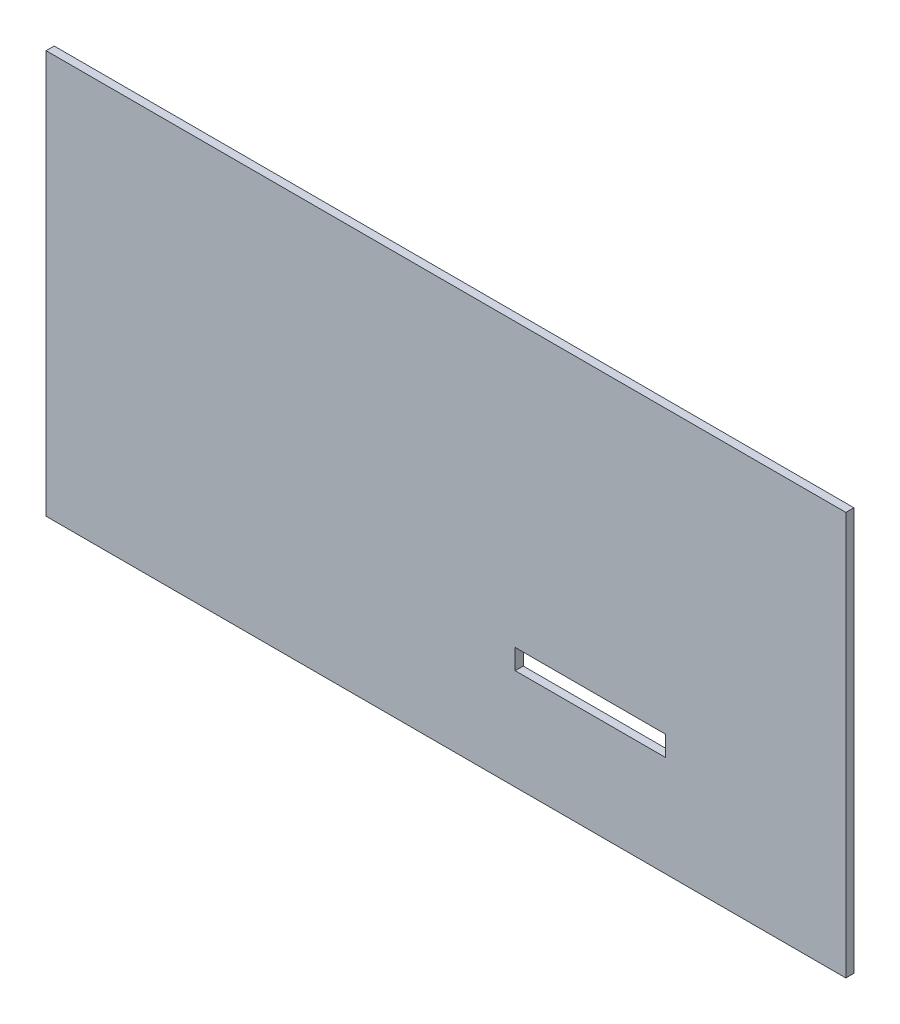
SolidWorks part; units mm, degrees
ref_plane "Спереди" through (0, 0, 0) normal (0, 0, 1) x (1, 0, 0)
ref_plane "Сверху" through (0, 0, 0) normal (0, 1, 0) x (1, 0, 0)
ref_plane "Справа" through (0, 0, 0) normal (1, 0, 0) x (0, 0, -1)
sketch "Эскиз1" plane through (0, 0, 0) normal (0, 0, 1) x (1, 0, 0)
  line L1 (-297.5, 150) -> (297.5, 150)
  line L2 (-297.5, 150) -> (-297.5, -150)
  line L3 (-297.5, -150) -> (297.5, -150)
  line L4 (297.5, 150) -> (297.5, -150)
  line L5 (-297.5, 150) -> (297.5, -150) construction
  line L6 (-297.5, -150) -> (297.5, 150) construction
  point P0 (0, 0)
  dimension "D1" = 595
  dimension "D2" = 300
extrude "Бобышка-Вытянуть1" add sketch "Эскиз1" along normal blind 6
sketch "Эскиз2" plane through (0, 0, 6) normal (0, 0, 1) x (1, 0, 0)
  line L0 (297.5, -150) -> (297.5, -75)
  line L1 (297.5, -150) -> (297.5, 150) construction
  line L2 (297.5, -75) -> (51.5, -75)
  line L3 (51.5, -60) -> (163.5, -60)
  line L4 (163.5, -60) -> (163.5, -75)
  line L5 (51.5, -60) -> (51.5, -75)
  dimension "D1" = 75
  dimension "D2" = 246
  dimension "D3" = 112
  dimension "D4" = 15
extrude "Вырез-Вытянуть1" cut sketch "Эскиз2" against normal through all contours L3 L5 L2 L4
